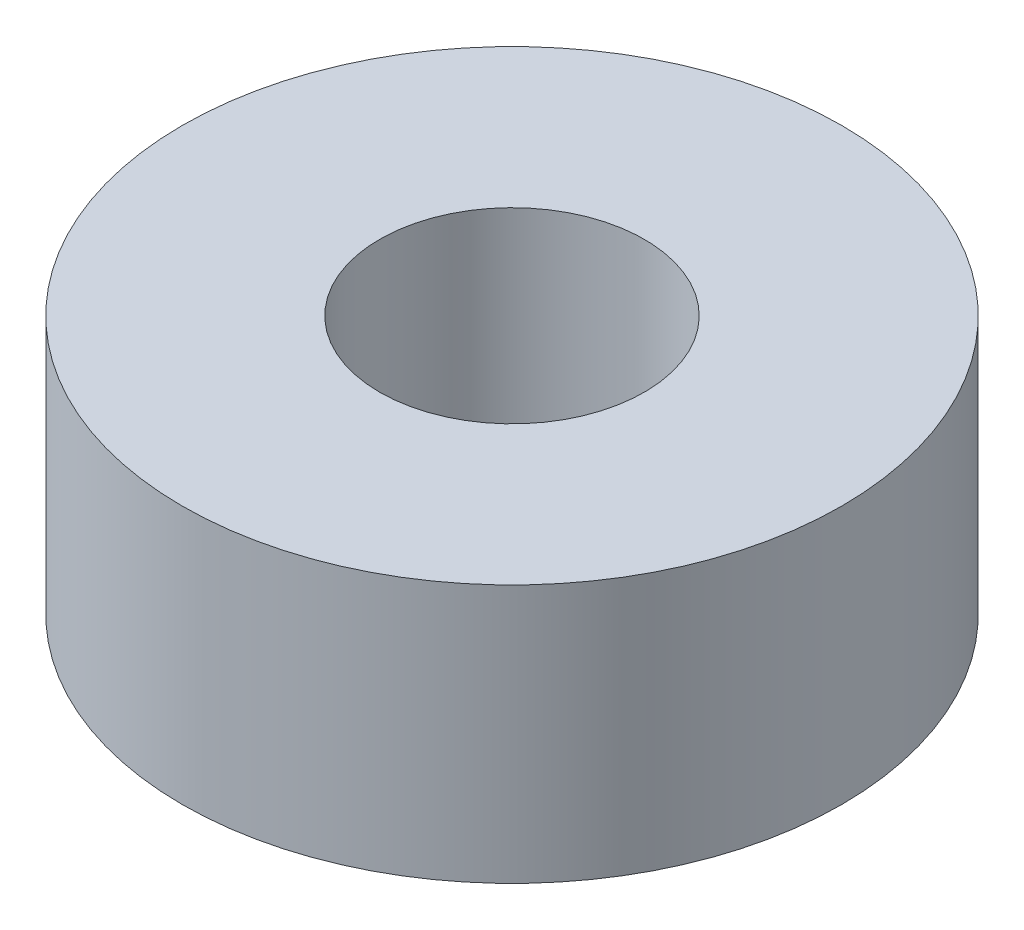
SolidWorks part; units mm, degrees
ref_plane "Front Plane" through (0, 0, 0) normal (0, 0, 1) x (1, 0, 0)
ref_plane "Top Plane" through (0, 0, 0) normal (0, 1, 0) x (1, 0, 0)
ref_plane "Right Plane" through (0, 0, 0) normal (1, 0, 0) x (0, 0, -1)
sketch "Sketch1" plane through (0, 0, 0) normal (0, 1, 0) x (1, 0, 0)
  circle A0 centre (0, 0) radius 6.35
  circle A1 centre (0, 0) radius 2.55
  dimension "D1" = 12.7
  dimension "D2" = 5.1
extrude "Boss-Extrude1" add sketch "Sketch1" along normal blind 4.9784
